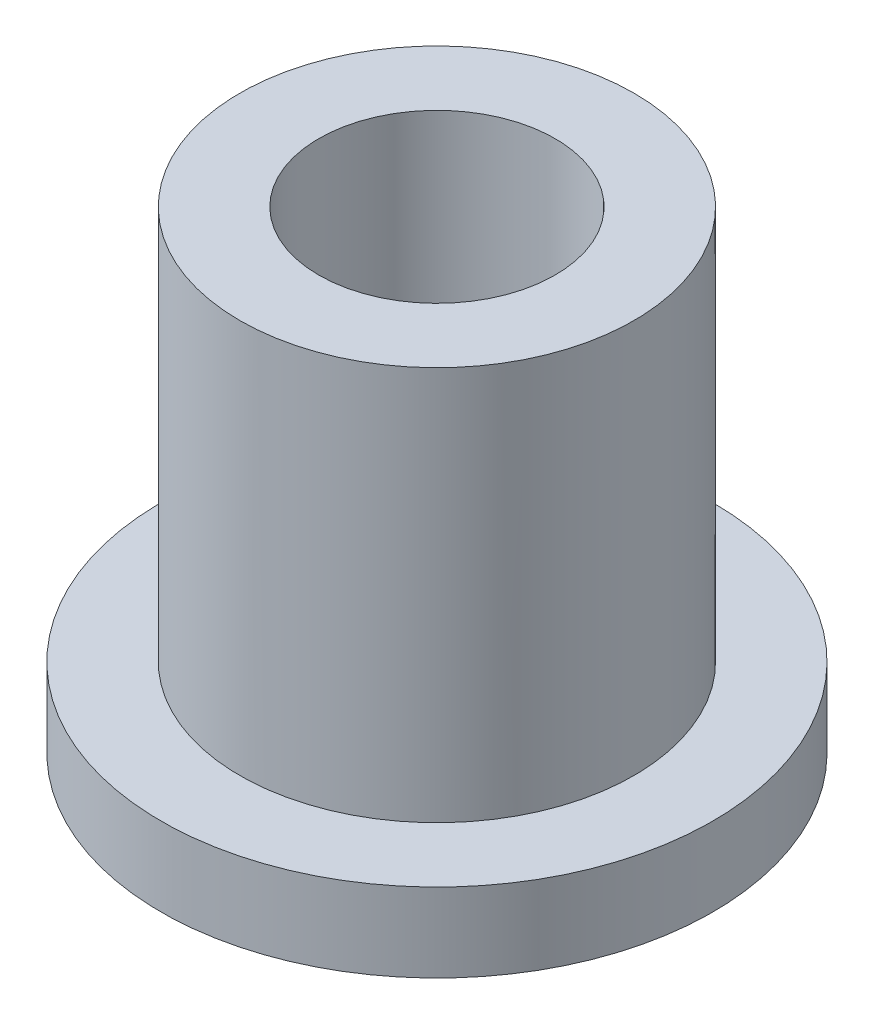
SolidWorks part; units mm, degrees
material "AISI 304"
ref_plane "前视基准面" through (0, 0, 0) normal (0, 0, 1) x (1, 0, 0)
ref_plane "上视基准面" through (0, 0, 0) normal (0, 1, 0) x (1, 0, 0)
ref_plane "右视基准面" through (0, 0, 0) normal (1, 0, 0) x (0, 0, -1)
other "Configuration Table"
sketch "草图1" plane through (0, 0, 0) normal (0, 1, 0) x (1, 0, 0)
  circle A0 centre (0, 0) radius 5
  circle A1 centre (0, 0) radius 3
  dimension "D1" = 10
  dimension "D2" = 6
extrude "凸台-拉伸1" add sketch "草图1" along normal blind 12
sketch "草图2" plane through (0, 0, 0) normal (0, -1, 0) x (1, 0, 0)
  circle A0 centre (0, 0) radius 7
  circle A1 centre (0, 0) radius 3
  dimension "D1" = 14
extrude "凸台-拉伸2" add sketch "草图2" against normal blind 2
